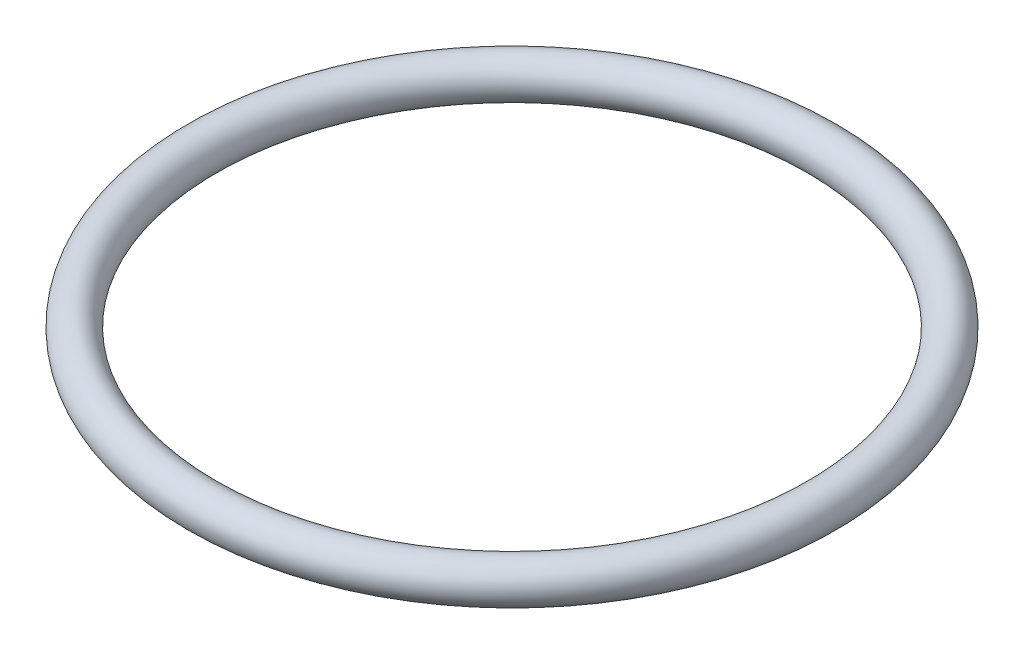
SolidWorks part; units mm, degrees
ref_plane "Plan de face" through (0, 0, 0) normal (0, 0, 1) x (1, 0, 0)
ref_plane "Plan de dessus" through (0, 0, 0) normal (0, 1, 0) x (1, 0, 0)
ref_plane "Plan de droite" through (0, 0, 0) normal (1, 0, 0) x (0, 0, -1)
sketch "Esquisse1" plane through (0, 0, 0) normal (0, 0, 1) x (1, 0, 0)
  line L0 (0, 10.8541) -> (0, -19.3759)
  circle A0 centre (22.42, 0) radius 1.45
  dimension "D1" = 2.9
  dimension "D2" = 22.42
revolve "Révolution1" add sketch "Esquisse1" angle 360 about L0
